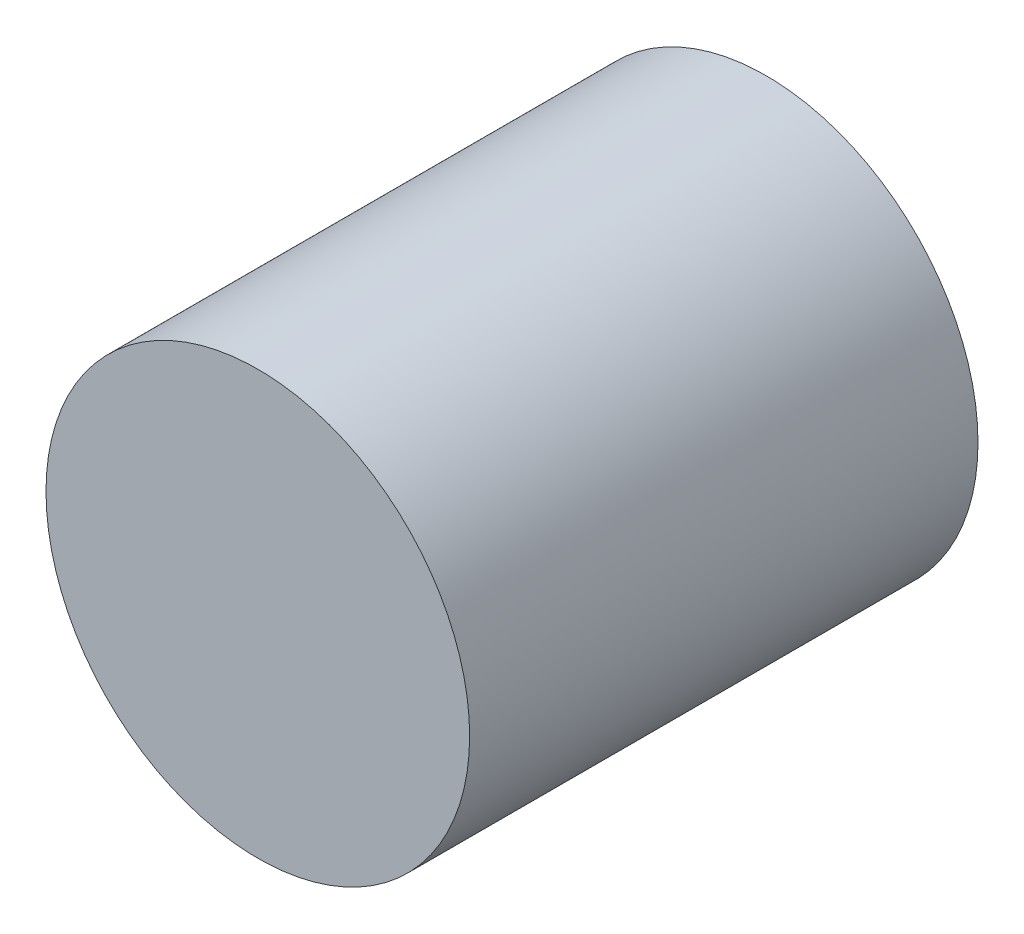
SolidWorks part; units mm, degrees
ref_plane "Спереди" through (0, 0, 0) normal (0, 0, 1) x (1, 0, 0)
ref_plane "Сверху" through (0, 0, 0) normal (0, 1, 0) x (1, 0, 0)
ref_plane "Справа" through (0, 0, 0) normal (1, 0, 0) x (0, 0, -1)
sketch "Эскиз1" plane through (0, 0, 0) normal (0, 0, 1) x (1, 0, 0)
  circle A0 centre (0, 0) radius 3.75
  dimension "D1" = 7.5
extrude "Вытянуть1" add sketch "Эскиз1" along normal blind 9
